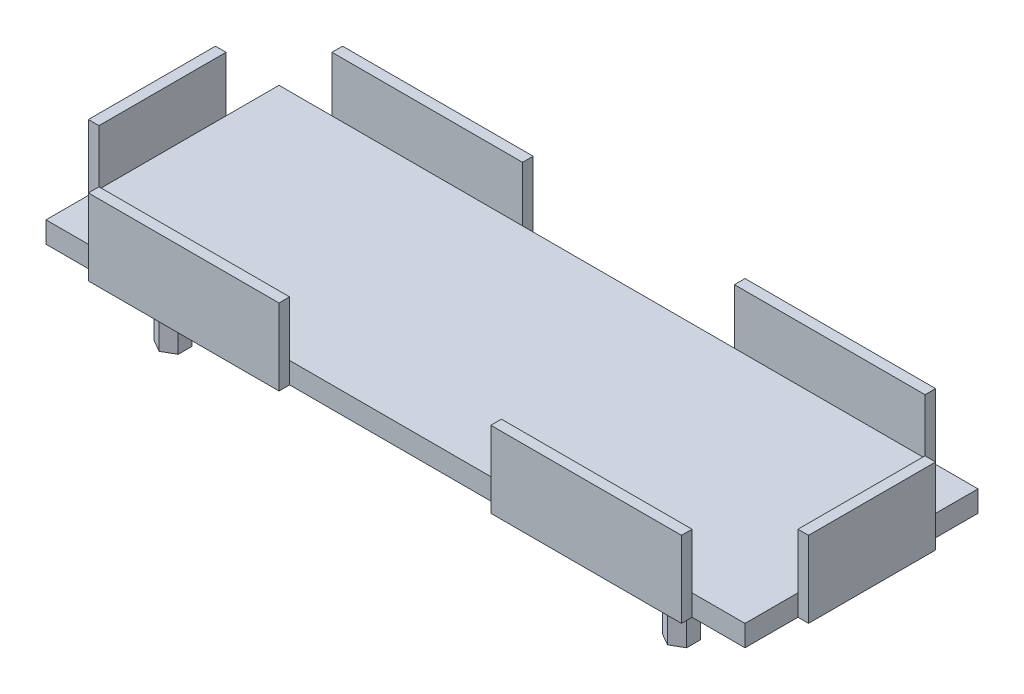
SolidWorks part; units mm, degrees
ref_plane "Front Plane" through (0, 0, 0) normal (0, 0, 1) x (1, 0, 0)
ref_plane "Top Plane" through (0, 0, 0) normal (0, 1, 0) x (1, 0, 0)
ref_plane "Right Plane" through (0, 0, 0) normal (1, 0, 0) x (0, 0, -1)
sketch "Sketch1" plane through (0, 0, 0) normal (0, 1, 0) x (1, 0, 0)
  line L0 (0, 0) -> (165, 0)
  line L1 (0, 0) -> (0, 55)
  line L2 (165, 0) -> (165, 55)
  line L3 (0, 55) -> (165, 55)
  dimension "D1" = 165
  dimension "D2" = 55
extrude "Boss-Extrude1" add sketch "Sketch1" along normal blind 5
sketch "Sketch2" plane through (0, 0, 0) normal (0, 1, 0) x (1, 0, 0)
  line L0 (0, 0) -> (0, 27.5) construction
  line L2 (0, 55) -> (0, 0) construction
  line L7 (0, 42.5) -> (0, 12.5) construction
  line L8 (167.5, 42.5) -> (165, 42.5)
  line L9 (0, 42.5) -> (-2.5, 42.5)
  line L10 (0, 42.5) -> (0, 12.5)
  line L11 (0, 12.5) -> (-2.5, 12.5)
  line L12 (-2.5, 42.5) -> (-2.5, 12.5)
  line L13 (165, 42.5) -> (165, 12.5)
  line L14 (167.5, 42.5) -> (167.5, 12.5)
  line L15 (167.5, 12.5) -> (165, 12.5)
  point P5 (0, 27.5)
  point P7 (0, 27.5)
  point P12 (165, 27.5)
  point P15 (167.5, 27.5)
  dimension "D1" = 30
  dimension "D2" = 2.5
  dimension "D3" = 2
  dimension "D4" = 165
extrude "Boss-Extrude2" add sketch "Sketch2" along normal blind 18
sketch "Sketch3" plane through (0, 0, 0) normal (0, 1, 0) x (1, 0, 0)
  line L0 (152.5, 55) -> (12.5, 55) construction
  line L1 (165, 55) -> (0, 55) construction
  line L2 (107.5, 57.5) -> (152.5, 57.5)
  line L3 (12.5, 55) -> (57.5, 55)
  line L4 (12.5, 55) -> (12.5, 57.5)
  line L5 (12.5, 57.5) -> (57.5, 57.5)
  line L6 (57.5, 55) -> (57.5, 57.5)
  line L7 (152.5, 55) -> (152.5, 57.5)
  line L8 (107.5, 55) -> (152.5, 55)
  line L9 (107.5, 55) -> (107.5, 57.5)
  line L10 (107.5, 0) -> (152.5, 0)
  line L11 (152.5, -2.5) -> (152.5, 0)
  line L12 (107.5, -2.5) -> (152.5, -2.5)
  line L13 (107.5, -2.5) -> (107.5, 0)
  line L14 (12.5, 0) -> (57.5, 0)
  line L15 (57.5, -2.5) -> (57.5, 0)
  line L16 (12.5, -2.5) -> (57.5, -2.5)
  line L17 (12.5, -2.5) -> (12.5, 0)
  point P5 (82.5, 55)
  dimension "D1" = 45
  dimension "D2" = 2.5
  dimension "D3" = 70
  dimension "D4" = 82.5
  dimension "D7" = 55
  dimension "D8" = 50
  dimension "D9" = 60
  dimension "D10" = 12.5
  dimension "D5" = 2
  dimension "D6" = 2
extrude "Boss-Extrude3" add sketch "Sketch3" along normal blind 18
sketch "Sketch4" plane through (0, 0, 0) normal (0, -1, 0) x (1, 0, 0)
  line L0 (0, 0) -> (165, -55) construction
  line L1 (22.5, -47.5) -> (142.5, -7.5) construction
  line L3 (139.65, -5.8546) -> (139.65, -9.1454)
  line L4 (139.65, -9.1454) -> (142.5, -10.7909)
  line L5 (22.5, -7.5) -> (142.5, -47.5) construction
  line L6 (142.5, -10.7909) -> (145.35, -9.1454)
  line L7 (145.35, -9.1454) -> (145.35, -5.8546)
  line L8 (145.35, -5.8546) -> (142.5, -4.2091)
  line L9 (142.5, -4.2091) -> (139.65, -5.8546)
  line L10 (22.5, -10.7909) -> (25.35, -9.1454)
  line L11 (25.35, -9.1454) -> (25.35, -5.8546)
  line L12 (25.35, -5.8546) -> (22.5, -4.2091)
  line L13 (22.5, -4.2091) -> (19.65, -5.8546)
  line L14 (19.65, -5.8546) -> (19.65, -9.1454)
  line L15 (19.65, -9.1454) -> (22.5, -10.7909)
  line L16 (22.5, -50.7909) -> (25.35, -49.1454)
  line L17 (25.35, -49.1454) -> (25.35, -45.8546)
  line L18 (25.35, -45.8546) -> (22.5, -44.2091)
  line L19 (22.5, -44.2091) -> (19.65, -45.8546)
  line L20 (19.65, -45.8546) -> (19.65, -49.1454)
  line L21 (19.65, -49.1454) -> (22.5, -50.7909)
  line L22 (145.35, -49.1454) -> (145.35, -45.8546)
  line L23 (145.35, -45.8546) -> (142.5, -44.2091)
  line L24 (142.5, -44.2091) -> (139.65, -45.8546)
  line L25 (139.65, -45.8546) -> (139.65, -49.1454)
  line L26 (139.65, -49.1454) -> (142.5, -50.7909)
  line L27 (142.5, -50.7909) -> (145.35, -49.1454)
  circle A0 centre (142.5, -7.5) radius 2.85 construction
  circle A1 centre (22.5, -7.5) radius 2.85 construction
  circle A2 centre (22.5, -47.5) radius 2.85 construction
  circle A3 centre (142.5, -47.5) radius 2.85 construction
  point P7 (82.5, -27.5)
  point P9 (82.5, -27.5)
  dimension "D1" = 120
  dimension "D2" = 40
  dimension "D3" = 5.7
extrude "Boss-Extrude4" add sketch "Sketch4" along normal blind 12.75
